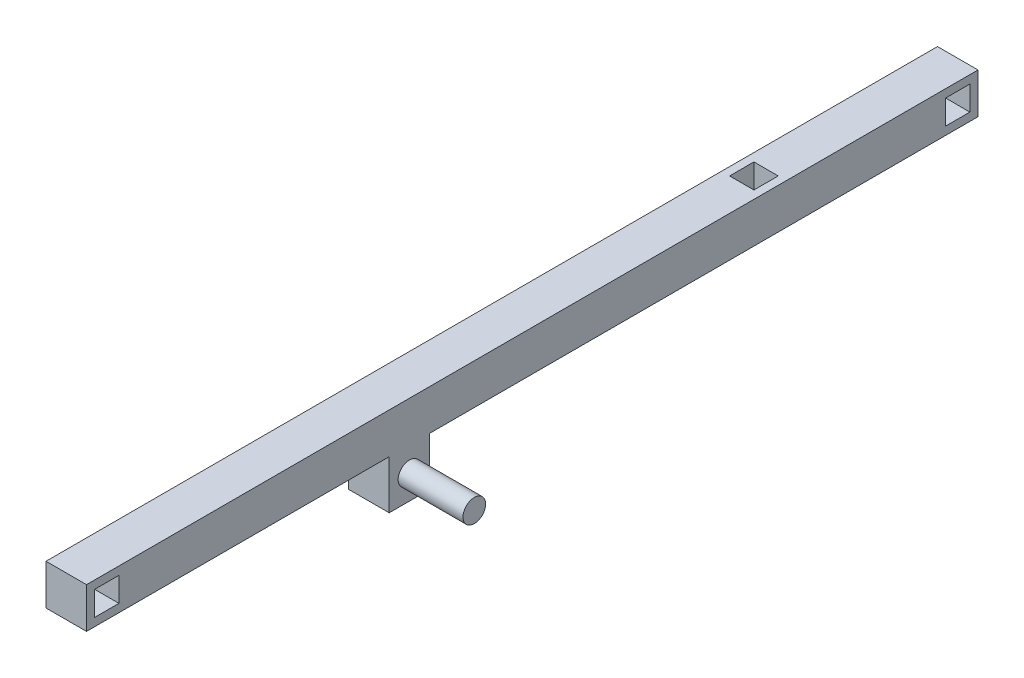
SolidWorks part; units mm, degrees
ref_plane "Front Plane" through (0, 0, 0) normal (0, 0, 1) x (1, 0, 0)
ref_plane "Top Plane" through (0, 0, 0) normal (0, 1, 0) x (1, 0, 0)
ref_plane "Right Plane" through (0, 0, 0) normal (1, 0, 0) x (0, 0, -1)
sketch "Sketch1" plane through (0, 0, 0) normal (0, 0, 1) x (1, 0, 0)
  line L1 (0, 0) -> (5, 0)
  line L2 (0, 0) -> (0, 5)
  line L3 (0, 5) -> (5, 5)
  line L4 (5, 0) -> (5, 5)
  dimension "D1" = 5
  dimension "D2" = 5
extrude "Boss-Extrude1" add sketch "Sketch1" along normal blind 110
sketch "Sketch2" plane through (0, 0, 0) normal (-1, 0, 0) x (0, 0, 1)
  line L0 (0, 5) -> (0, 0) construction
  line L1 (1, 1) -> (4, 1)
  line L2 (1, 1) -> (1, 4)
  line L3 (1, 4) -> (4, 4)
  line L4 (4, 1) -> (4, 4)
  line L5 (110, 5) -> (0, 5) construction
  line L6 (110, 5) -> (110, 0) construction
  line L7 (109, 4) -> (106, 4)
  line L8 (109, 4) -> (109, 1)
  line L9 (109, 1) -> (106, 1)
  line L10 (106, 4) -> (106, 1)
  dimension "D1" = 3
  dimension "D2" = 3
  dimension "D3" = 1
  dimension "D4" = 1
  dimension "D5" = 3
  dimension "D6" = 3
  dimension "D7" = 1
  dimension "D8" = 1
extrude "Cut-Extrude1" cut sketch "Sketch2" against normal blind 9
sketch "Sketch3" plane through (0, 5, 0) normal (0, 1, 0) x (1, 0, 0)
  line L0 (0, -110) -> (0, 0) construction
  line L1 (1, -23.65) -> (4, -23.65)
  line L2 (1, -23.65) -> (1, -26.65)
  line L3 (1, -26.65) -> (4, -26.65)
  line L4 (4, -23.65) -> (4, -26.65)
  line L5 (1, -26.65) -> (4, -23.65) construction
  line L6 (1, -23.65) -> (4, -26.65) construction
  line L7 (5, 0) -> (0, 0) construction
  point P6 (2.5, -25.15)
  dimension "D1" = 3
  dimension "D2" = 3
  dimension "D3" = 1
  dimension "D4" = 4.2426
  dimension "D5" = 4.2426
  dimension "D6" = 25.15
extrude "Cut-Extrude2" cut sketch "Sketch3" against normal blind 9
sketch "Sketch4" plane through (0, 0, 0) normal (0, -1, 0) x (-1, 0, 0)
  line L0 (-5, -110) -> (-5, 0) construction
  line L1 (-5, -67.65) -> (0, -67.65)
  line L2 (-5, -67.65) -> (-5, -72.65)
  line L3 (-5, -72.65) -> (0, -72.65)
  line L4 (0, -67.65) -> (0, -72.65)
  line L5 (0, -110) -> (0, 0) construction
  line L6 (-5, -72.65) -> (0, -67.65) construction
  line L7 (-5, -67.65) -> (0, -72.65) construction
  line L8 (-4, -26.65) -> (-1, -23.65) construction
  line L9 (-4, -23.65) -> (-1, -26.65) construction
  point P20 (-2.5, -25.15)
  point P21 (-2.5, -70.15)
  dimension "D1" = 5
  dimension "D2" = 7.0711
  dimension "D3" = 7.0711
  dimension "D4" = 4.2426
  dimension "D5" = 4.2426
  dimension "D6" = 45
extrude "Boss-Extrude2" add sketch "Sketch4" along normal blind 6
sketch "Sketch5" plane through (0, 0, 0) normal (-1, 0, 0) x (0, 0, 1)
  line L0 (72.65, -6) -> (72.65, 0) construction
  line L1 (110, 0) -> (72.65, 0) construction
  circle A0 centre (70.15, -3) radius 1.4
  dimension "D1" = 2.8
  dimension "D2" = 2.5
  dimension "D3" = 3
extrude "Boss-Extrude3" add sketch "Sketch5" against normal blind 13
